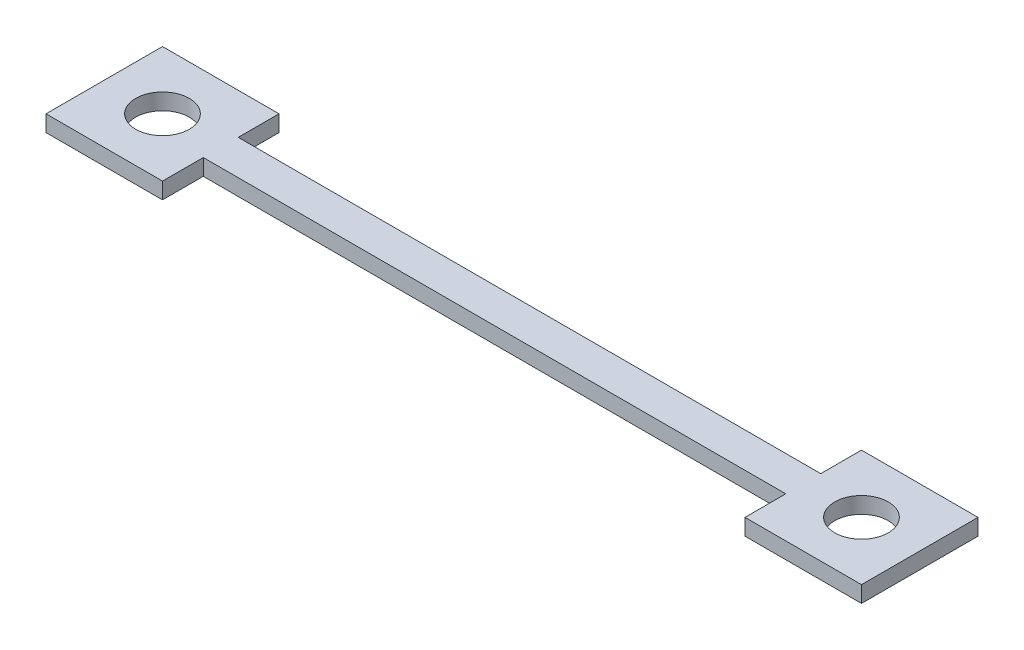
SolidWorks part; units mm, degrees
material "Commercially Pure CP-Ti UNS R50400 (SS)"
ref_plane "Front Plane" through (0, 0, 0) normal (0, 0, 1) x (1, 0, 0)
ref_plane "Top Plane" through (0, 0, 0) normal (0, 1, 0) x (1, 0, 0)
ref_plane "Right Plane" through (0, 0, 0) normal (1, 0, 0) x (0, 0, -1)
sketch "Sketch1" plane through (0, 0, 0) normal (0, 1, 0) x (1, 0, 0)
  line L0 (-41.424, -10.2833) -> (-41.424, -12.5058)
  line L1 (-47.774, -12.5058) -> (-41.424, -12.5058)
  line L2 (-47.774, -12.5058) -> (-47.774, -6.1558)
  line L3 (-47.774, -6.1558) -> (-41.424, -6.1558)
  line L4 (-3.324, -12.5058) -> (-3.324, -6.1558)
  line L7 (-41.424, -10.2833) -> (-9.674, -10.2833)
  line L9 (-41.424, -8.3783) -> (-9.674, -8.3783)
  line L13 (-41.424, -8.3783) -> (-41.424, -6.1558)
  line L14 (-9.674, -8.3783) -> (-9.674, -6.1558)
  line L15 (-9.674, -10.2833) -> (-9.674, -12.5058)
  line L16 (-9.674, -6.1558) -> (-3.324, -6.1558)
  line L17 (-9.674, -12.5058) -> (-3.324, -12.5058)
  point P0 (0, 0)
  point P6 (0, 0)
  dimension "D1" = 44.45
  dimension "D2" = 6.35
  dimension "D3" = 6.35
  dimension "D4" = 1.905
extrude "Boss-Extrude1" add sketch "Sketch1" along normal mid plane 0.889
hole_wizard "#97 (0.0059) Diameter Hole1" positions "Sketch4" profile "Sketch3" hole size "#97" standard "Ansi Inch" end condition through all
sketch "Sketch4" plane through (0, 0.4445, 0) normal (0, 1, 0) x (-1, 0, 0)
  line L0 (47.774, 12.5058) -> (41.424, 6.1558) construction
  point P0 (44.599, 9.3308)
sketch "Sketch3" plane through (-44.599, 0.4445, 9.3308) normal (1, 0, 0) x (0, 0, 1)
  line L0 (0, 0) -> (0, 0.889)
  line L1 (0, 0.889) -> (1.4605, 0.889)
  line L2 (1.4605, 0.889) -> (1.4605, 0)
  line L5 (1.4605, 0) -> (0, 0)
  line L11 (0, -6.35) -> (0, 107.95) construction
  dimension "Thru Hole Dia." = 2.921
  dimension "Thru Hole Depth" = 0.889
ref_plane "Plane1" through (-25.549, 0, 0) normal (1, 0, 0) x (0, 0, -1)
mirror "Mirror1" about plane through (-25.549, 0, 0) normal (1, 0, 0) of "#97 (0.0059) Diameter Hole1"
